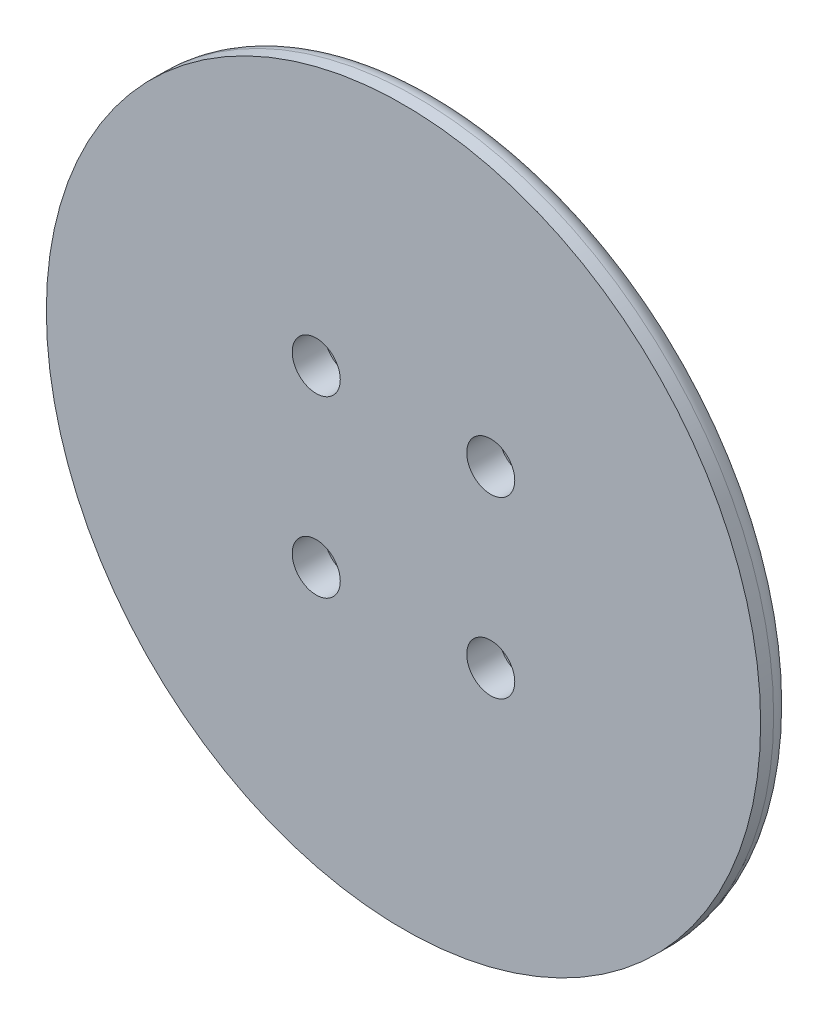
SolidWorks part; units mm, degrees
ref_plane "前视基准面" through (0, 0, 0) normal (0, 0, 1) x (1, 0, 0)
ref_plane "上视基准面" through (0, 0, 0) normal (0, 1, 0) x (1, 0, 0)
ref_plane "右视基准面" through (0, 0, 0) normal (1, 0, 0) x (0, 0, -1)
other "Configuration Table"
sketch "草图1" plane through (0, 0, 0) normal (0, 0, 1) x (1, 0, 0)
  circle A1 centre (0, 0) radius 28.5 construction
  circle A6 centre (0, 0) radius 32.5
  circle A18 centre (-13.435, -13.435) radius 1.5 construction
  circle A19 centre (13.435, -13.435) radius 1.5 construction
  circle A20 centre (13.435, 13.435) radius 1.5 construction
  circle A21 centre (-13.435, 13.435) radius 1.5 construction
  circle A22 centre (-13.435, 13.435) radius 1.7
  circle A23 centre (-13.435, -13.435) radius 1.7
  circle A24 centre (13.435, -13.435) radius 1.7
  circle A25 centre (13.435, 13.435) radius 1.7
  point P1 (0, 0)
  dimension "D1" = 0.2
  dimension "D2" = 65
  dimension "D3" = 3.4
extrude "凸台-拉伸1" add sketch "草图1" along normal blind 5
sketch "草图2" plane through (0, 0, 5) normal (0, 0, 1) x (1, 0, 0)
  circle A1 centre (-13.435, -13.435) radius 1.7 construction
  circle A2 centre (13.435, -13.435) radius 3.7
  circle A3 centre (13.435, -13.435) radius 3.7
  circle A4 centre (-13.435, 13.435) radius 1.7 construction
  circle A5 centre (13.435, 13.435) radius 1.7 construction
  circle A9 centre (-13.435, -13.435) radius 1.7 construction
  circle A10 centre (-13.435, 13.435) radius 1.7 construction
  circle A11 centre (13.435, 13.435) radius 1.7 construction
  circle A12 centre (-13.435, 13.435) radius 3.7
  circle A13 centre (-13.435, -13.435) radius 3.7
  circle A14 centre (13.435, 13.435) radius 3.7
  circle A15 centre (0, 0) radius 55
  dimension "D2" = 2
  dimension "D3" = 110
  dimension "D1" = 2
extrude "凸台-拉伸2" add sketch "草图2" along normal blind 5
fillet "圆角2" radius 3 1 edges at (32.5, 0, 0)
fillet "圆角3" radius 3 1 edges at (55, 0, 5)
